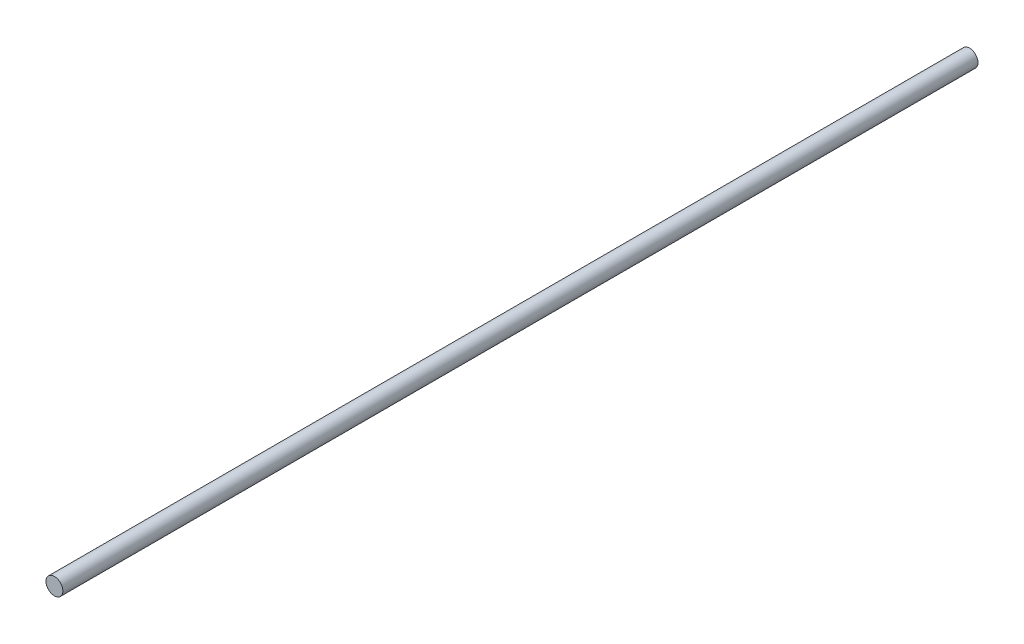
SolidWorks part; units mm, degrees
material "Oak"
ref_plane "Front Plane" through (0, 0, 0) normal (0, 0, 1) x (1, 0, 0)
ref_plane "Top Plane" through (0, 0, 0) normal (0, 1, 0) x (1, 0, 0)
ref_plane "Right Plane" through (0, 0, 0) normal (1, 0, 0) x (0, 0, -1)
sketch "Sketch1" plane through (0, 0, 0) normal (0, 0, 1) x (1, 0, 0)
  circle A0 centre (0, 0) radius 725.805
  dimension "D1" = 1451.61
extrude "Boss-Extrude1" add sketch "Sketch1" along normal blind 78740
scale "Scale1" scale about centroid uniform scaling yes scale factor 0.03937
